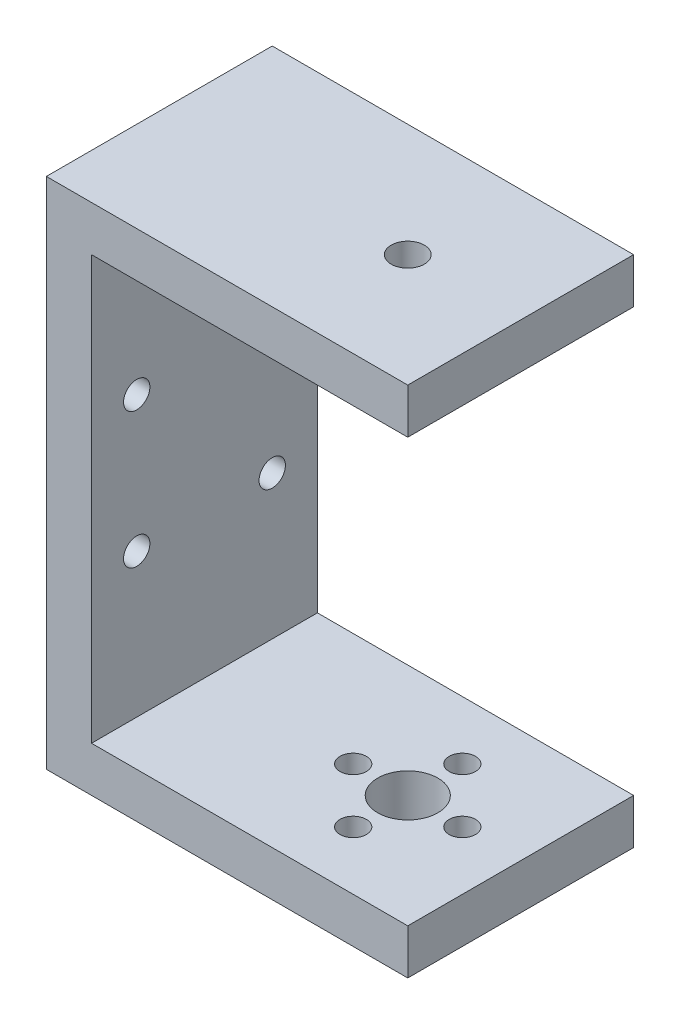
SolidWorks part; units mm, degrees
ref_plane "Front Plane" through (0, 0, 0) normal (0, 0, 1) x (1, 0, 0)
ref_plane "Top Plane" through (0, 0, 0) normal (0, 1, 0) x (1, 0, 0)
ref_plane "Right Plane" through (0, 0, 0) normal (1, 0, 0) x (0, 0, -1)
sketch "Sketch1" plane through (0, 0, 0) normal (0, 0, 1) x (1, 0, 0)
  line L1 (-24, -34.1) -> (24, -34.1)
  line L2 (-24, -34.1) -> (-24, 34.1)
  line L3 (-24, 34.1) -> (24, 34.1)
  line L4 (24, -34.1) -> (24, 34.1)
  line L5 (-24, -34.1) -> (24, 34.1) construction
  line L6 (-24, 34.1) -> (24, -34.1) construction
  point P0 (0, 0)
  dimension "D1" = 48
  dimension "D2" = 68.2
extrude "Boss-Extrude1" add sketch "Sketch1" along normal blind 30
sketch "Sketch2" plane through (0, 0, 30) normal (0, 0, 1) x (1, 0, 0)
  line L0 (24, -34.1) -> (24, 34.1) construction
  line L1 (-18, 28.1) -> (24, 28.1)
  line L2 (-18, 28.1) -> (-18, -28.1)
  line L3 (-18, -28.1) -> (24, -28.1)
  line L4 (24, 28.1) -> (24, -28.1)
  line L5 (-18, -28.1) -> (24, -28.1) construction
extrude "Cut-Extrude1" cut sketch "Sketch2" against normal through all
sketch "Sketch4" plane through (0, -34.1, 0) normal (0, -1, 0) x (1, 0, 0)
  circle A0 centre (9, 15) radius 4
  circle A1 centre (9, 22.25) radius 1.75
  circle A2 centre (16.25, 15) radius 1.75
  circle A3 centre (9, 7.75) radius 1.75
  circle A4 centre (1.75, 15) radius 1.75
extrude "Cut-Extrude3" cut sketch "Sketch4" against normal blind 30
sketch "Sketch5" plane through (0, 34.1, 0) normal (0, 1, 0) x (1, 0, 0)
  circle A0 centre (9, -15) radius 2.2
extrude "Cut-Extrude4" cut sketch "Sketch5" against normal blind 30
sketch "Sketch6" plane through (-18, 0, 0) normal (1, 0, 0) x (0, 0, -1)
  line L0 (0, 0) -> (-30, 0) construction
  line L1 (0, 28.1) -> (0, -28.1) construction
  line L2 (-30, 28.1) -> (-30, -28.1) construction
  line L3 (-15, 28.1) -> (-15, -28.1) construction
  line L4 (0, 28.1) -> (-30, 28.1) construction
  line L5 (0, -28.1) -> (-30, -28.1) construction
  circle A0 centre (-24, -9) radius 1.75
  circle A1 centre (-6, -9) radius 1.75
  circle A2 centre (-6, 9) radius 1.75
  circle A3 centre (-24, 9) radius 1.75
  dimension "D1" = 3.5
  dimension "D2" = 9
  dimension "D3" = 9
extrude "Cut-Extrude5" cut sketch "Sketch6" against normal through all
